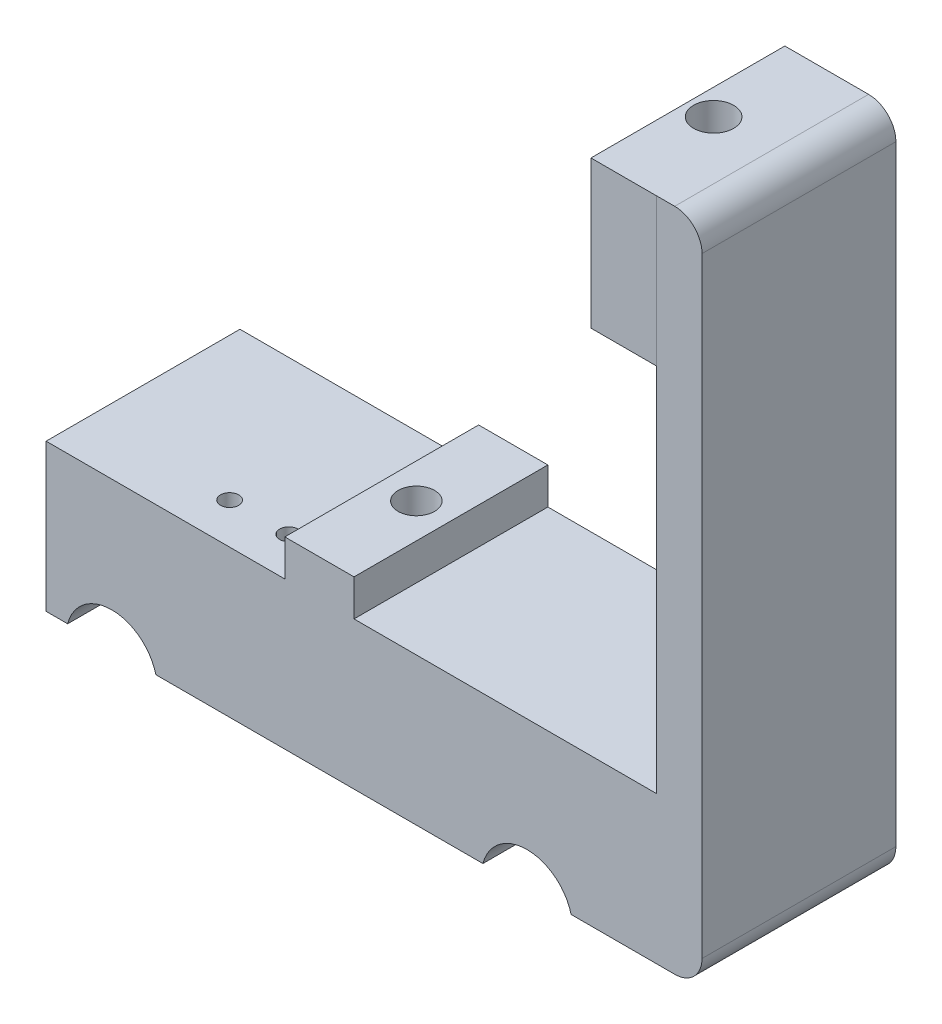
SolidWorks part; units mm, degrees
ref_plane "Front Plane" through (0, 0, 0) normal (0, 0, 1) x (1, 0, 0)
ref_plane "Top Plane" through (0, 0, 0) normal (0, 1, 0) x (1, 0, 0)
ref_plane "Right Plane" through (0, 0, 0) normal (1, 0, 0) x (0, 0, -1)
sketch "Sketch2" plane through (0, 0, 0) normal (0, 0, 1) x (1, 0, 0)
  line L0 (10.1, 0) -> (-10.1, 0)
  line L1 (-10.1, 0) -> (-10.1, 1.7099)
  line L2 (-10.1, 1.7099) -> (-6.2548, 7)
  line L3 (-6.2548, 7) -> (6.2548, 7)
  line L4 (0, 7) -> (0, 0)
  line L5 (0, 0) -> (0, 9.2516) construction
  line L6 (10.1, 1.7099) -> (6.2548, 7)
  line L7 (10.1, 0) -> (10.1, 1.7099)
  dimension "D1" = 20.2
  dimension "D2" = 7
extrude "Boss-Extrude1" add sketch "Sketch2" along normal blind 10.8 contours L4 L3 L2 L1 L0 | L0 L7 L6 L3 L4
sketch "Sketch4" plane through (0, 0, 0) normal (0, 0, 1) x (1, 0, 0)
  line L0 (-3.8, 0) -> (-3.8, -4.8)
  line L1 (10.1, 0) -> (-10.1, 0) construction
  line L2 (-3.8, -4.8) -> (-30, -4.8)
  line L3 (-30, -4.8) -> (-30, -29.8)
  line L4 (-30, -29.8) -> (30, -29.8)
  line L5 (0, 0) -> (0, -29.8) construction
  line L6 (0, -29.8) -> (0, 0)
  line L7 (3.8, 0) -> (-3.8, 0)
  line L8 (0, 0) -> (0, -30.5381) construction
  line L9 (30, -4.8) -> (30, -29.8)
  line L10 (3.8, -4.8) -> (30, -4.8)
  line L11 (3.8, 0) -> (3.8, -4.8)
  line L13 (-30, -20.98) -> (30, -20.98)
  line L14 (-30, -20.98) -> (-30, -23.48)
  line L15 (-30, -23.48) -> (30, -23.48)
  line L16 (30, -20.98) -> (30, -23.48)
  dimension "D1" = 4.8
  dimension "D2" = 3.8
  dimension "D3" = 25
  dimension "D4" = 60
  dimension "D6" = 8.82
extrude "Boss-Extrude2" add sketch "Sketch4" along normal mid plane 21.28 contours L6 L7 L0 L2 L3 L4 | L11 L7 L6 L4 L9 L10
sketch "Sketch5" plane through (0, 0, 0) normal (0, 0, 1) x (1, 0, 0)
  line L0 (-29.791, -22.2274) -> (26.9734, -22.2274) construction
  line L3 (0, -20.98) -> (0, 7) construction
  line L5 (-6.2548, 7) -> (6.2548, 7) construction
  line L20 (-30, -20.98) -> (30, -20.98) construction
  circle A0 centre (-22.791, -22.2274) radius 5
  circle A1 centre (22.791, -22.2274) radius 5
  dimension "D1" = 7
extrude "Cut-Extrude1" cut sketch "Sketch5" along normal through all both and the other way through all
fillet "Fillet1" radius 1 6 edges at (-10.1, 0, 5.4) (-10.1, 1.7099, 5.4) (-6.2548, 7, 5.4) (6.2548, 7, 5.4) (10.1, 0, 5.4) (10.1, 1.7099, 5.4)
sketch "Sketch6" plane through (30, 0, 0) normal (1, 0, 0) x (0, 0, -1)
  line L0 (-10.64, -20.98) -> (10.64, -20.98) construction
  line L1 (-10.64, -4.8) -> (10.64, -4.8)
  line L2 (-10.64, -4.8) -> (-10.64, -20.98)
  line L3 (-10.64, -20.98) -> (10.64, -20.98)
  line L4 (10.64, -4.8) -> (10.64, -20.98)
extrude "Boss-Extrude3" add sketch "Sketch6" along normal blind 12
sketch "Sketch7" plane through (0, -4.8, 0) normal (0, 1, 0) x (1, 0, 0)
  line L0 (3.8, -10.64) -> (42, -10.64) construction
  line L1 (42, 10.6413) -> (37, 10.6413)
  line L2 (42, 10.6413) -> (42, -10.64)
  line L3 (42, -10.64) -> (37, -10.64)
  line L4 (37, 10.6413) -> (37, -10.64)
  dimension "D1" = 5
extrude "Boss-Extrude4" add sketch "Sketch7" along normal blind 56.83
sketch "Sketch8" plane through (37, 0, 0) normal (-1, 0, 0) x (0, 0, 1)
  line L0 (-10.6413, 52.03) -> (-10.6413, -4.8) construction
  line L1 (10.643, 52.03) -> (-10.6413, 52.03)
  line L2 (10.643, 52.03) -> (10.643, 35.85)
  line L3 (10.643, 35.85) -> (-10.6413, 35.85)
  line L4 (-10.6413, 52.03) -> (-10.6413, 35.85)
  dimension "D1" = 16.18
extrude "Boss-Extrude5" add sketch "Sketch8" along normal blind 7.19
fillet "Fillet3" radius 3 2 edges at (42, 52.03, -0.0007) (42, -20.98, 0)
sketch "Sketch9" plane through (0, -20.98, 0) normal (0, -1, 0) x (1, 0, 0)
  line L0 (27.6329, 0) -> (27.6329, 10.8) construction
  line L2 (27.6329, 10.64) -> (39, 10.64) construction
  circle A0 centre (32.6329, 0) radius 2.2
  dimension "D1" = 5
  dimension "D2" = 10.64
extrude "Cut-Extrude2" cut sketch "Sketch9" against normal through all
sketch "Sketch10" plane through (0, -20.98, 0) normal (0, -1, 0) x (1, 0, 0)
  line L2 (-17.9491, 0) -> (-17.9491, 10.8) construction
  line L3 (-17.9491, 10.64) -> (17.9491, 10.64) construction
  circle A0 centre (0.0009, 0) radius 2
  dimension "D1" = 10.64
  dimension "D2" = 17.95
extrude "Cut-Extrude3" cut sketch "Sketch10" against normal through all
sketch "Sketch11" plane through (0, 0, 10.8) normal (0, 0, 1) x (1, 0, 0)
  line L0 (9.1, 0) -> (-9.1, 0) construction
  line L1 (-12.6098, 8.9215) -> (12.3675, 8.9215)
  line L2 (-12.6098, 8.9215) -> (-12.6098, -0.8)
  line L3 (-12.6098, -0.8) -> (12.3675, -0.8)
  line L4 (12.3675, 8.9215) -> (12.3675, -0.8)
  dimension "D1" = 0.8
extrude "Cut-Extrude4" cut sketch "Sketch11" against normal through all
sketch "Sketch13" plane through (0, -20.98, 0) normal (0, -1, 0) x (1, 0, 0)
  arc A0 (-8.8274, 6.1704) -> (-6.8274, 6.1704) centre (-7.8274, 6.1704) ccw construction
  arc A1 (-6.8274, 6.1704) -> (-8.8274, 6.1704) centre (-7.8274, 6.1704) ccw construction
  arc A2 (-13.3274, 6.1704) -> (-15.3274, 6.1704) centre (-14.3274, 6.1704) ccw construction
  arc A3 (-15.3274, 6.1704) -> (-13.3274, 6.1704) centre (-14.3274, 6.1704) ccw construction
  arc A4 (-8.8274, 6.1704) -> (-6.8274, 6.1704) centre (-7.8274, 6.1704) ccw
  arc A5 (-6.8274, 6.1704) -> (-8.8274, 6.1704) centre (-7.8274, 6.1704) ccw
  arc A6 (-13.3274, 6.1704) -> (-15.3274, 6.1704) centre (-14.3274, 6.1704) ccw
  arc A7 (-15.3274, 6.1704) -> (-13.3274, 6.1704) centre (-14.3274, 6.1704) ccw
extrude "Cut-Extrude5" cut sketch "Sketch13" against normal up to next
